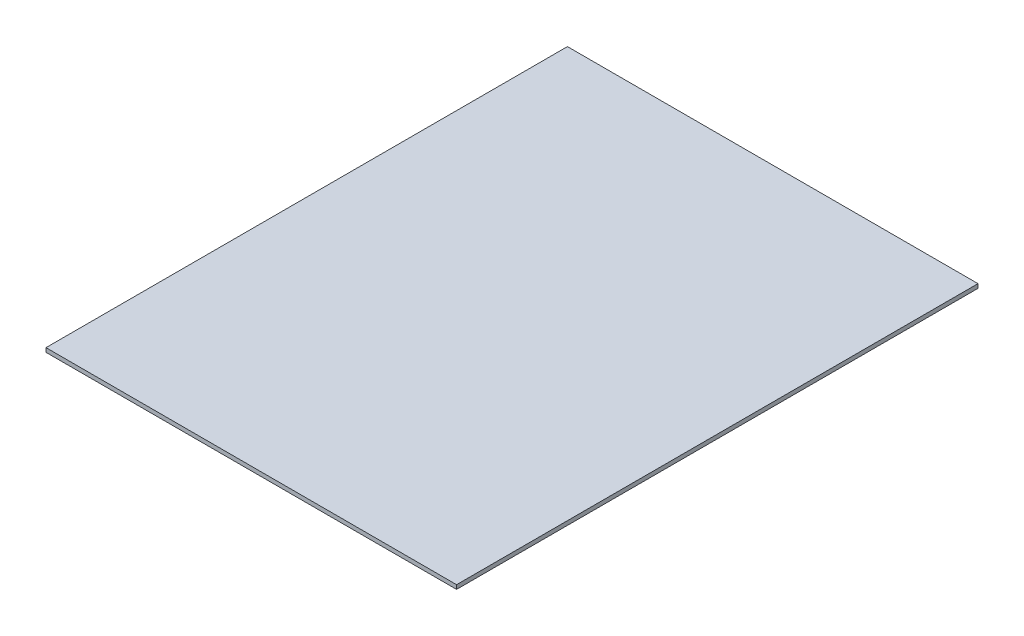
SolidWorks part; units mm, degrees
material "PVC Rigid"
ref_plane "Front Plane" through (0, 0, 0) normal (0, 0, 1) x (1, 0, 0)
ref_plane "Top Plane" through (0, 0, 0) normal (0, 1, 0) x (1, 0, 0)
ref_plane "Right Plane" through (0, 0, 0) normal (1, 0, 0) x (0, 0, -1)
sketch "Sketch1" plane through (0, 0, 0) normal (0, 1, 0) x (1, 0, 0)
  line L0 (0, 190.5) -> (0, 0) construction
  line L1 (-150, -190.5) -> (150, -190.5)
  line L2 (-150, -190.5) -> (-150, 190.5)
  line L3 (-150, 190.5) -> (150, 190.5)
  line L4 (150, -190.5) -> (150, 190.5)
  line L5 (0, 0) -> (150, 0) construction
  dimension "D1" = 381
  dimension "D2" = 300
extrude "Boss-Extrude1" add sketch "Sketch1" along normal blind 3
